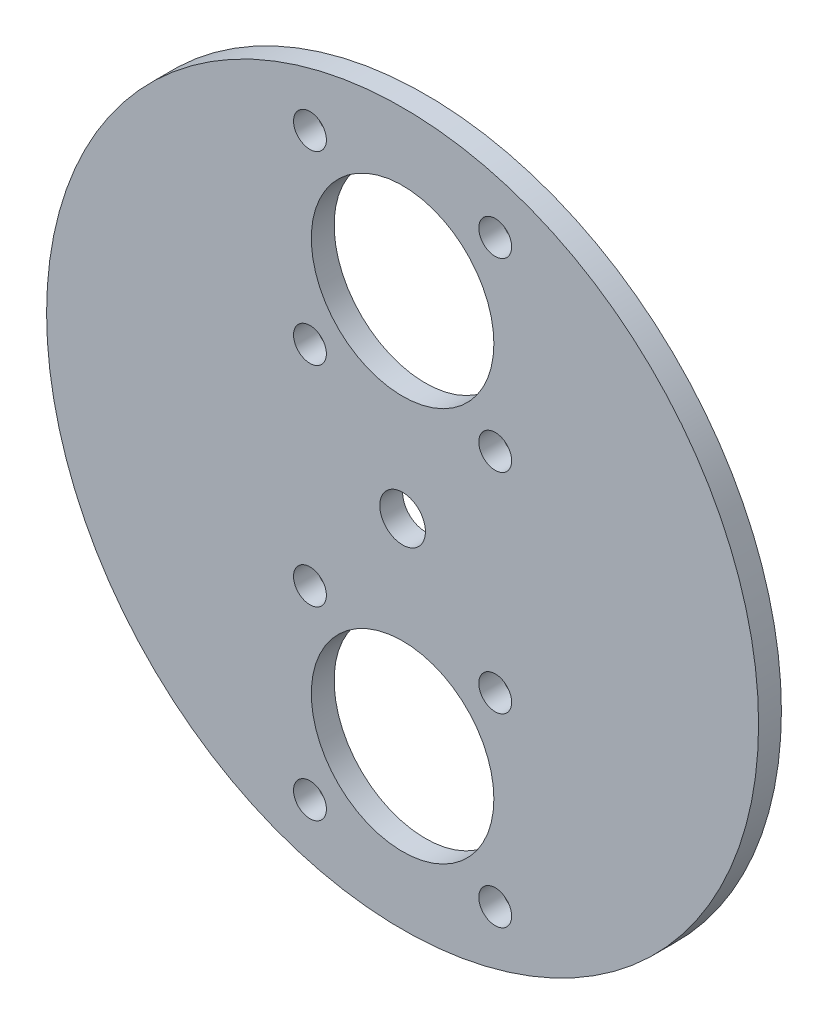
SolidWorks part; units mm, degrees
ref_plane "Front Plane" through (0, 0, 0) normal (0, 0, 1) x (1, 0, 0)
ref_plane "Top Plane" through (0, 0, 0) normal (0, 1, 0) x (1, 0, 0)
ref_plane "Right Plane" through (0, 0, 0) normal (1, 0, 0) x (0, 0, -1)
sketch "Sketch1" plane through (0, 0, 0) normal (0, 0, 1) x (1, 0, 0)
  line L0 (0, 49.53) -> (0, -49.53) construction
  circle A0 centre (0, 0) radius 49.53
  dimension "D1" = 99.06
extrude "Boss-Extrude1" add sketch "Sketch1" along normal blind 3.175 contours A0
sketch "Sketch2" plane through (0, 0, 3.175) normal (0, 0, 1) x (1, 0, 0)
  line L0 (0, 49.53) -> (0, -49.53) construction
  circle A0 centre (0, 0) radius 49.53 construction
  circle A1 centre (0, 27.432) radius 12.7
  circle A2 centre (0, -27.432) radius 12.7
  dimension "D1" = 25.4
  dimension "D2" = 25.4
  dimension "D3" = 27.432
  dimension "D4" = 27.432
extrude "Cut-Extrude1" cut sketch "Sketch2" against normal up to surface (3.175 mm away) up to face at (49.53, 0, 0)
sketch "Sketch3" plane through (0, 0, 3.175) normal (0, 0, 1) x (1, 0, 0)
  circle A0 centre (0, 0) radius 3.175
  dimension "D1" = 6.35
extrude "Cut-Extrude2" cut sketch "Sketch3" against normal up to surface (3.175 mm away) contours A0 up to face at (12.7, 27.432, 0)
sketch "Sketch5" plane through (0, 0, 0) normal (0, 0, -1) x (-1, 0, 0)
  line L0 (-12.8867, -14.5453) -> (0, -27.432) construction
  line L1 (0, 49.53) -> (0, -49.53) construction
  circle A0 centre (0, -27.432) radius 18.2245 construction
  circle A1 centre (-12.8867, -14.5453) radius 2.286
  dimension "D1" = 36.449
  dimension "D3" = 4.572
  dimension "D2" = 45
extrude "Cut-Extrude3" cut sketch "Sketch5" against normal up to surface (3.175 mm away) contours A1 up to face at (3.175, 0, 3.175)
pattern_circular "CirPattern1" count 4 over 360 about axis through (0, -27.432, 0) along (0, 0, 1) of "Cut-Extrude3"
sketch "Sketch6" plane through (0, 0, 0) normal (0, 0, -1) x (-1, 0, 0)
  line L0 (0, 27.432) -> (12.8867, 14.5453) construction
  line L1 (0, 49.53) -> (0, -49.53) construction
  circle A0 centre (0, 27.432) radius 18.2245 construction
  circle A1 centre (12.8867, 14.5453) radius 2.286
  dimension "D1" = 36.449
  dimension "D2" = 4.572
  dimension "D3" = 45
extrude "Cut-Extrude4" cut sketch "Sketch6" against normal up to surface (3.175 mm away) contours A1 up to face at (15.1727, -40.3187, 3.175)
pattern_circular "CirPattern2" count 4 over 360 about axis through (0, 27.432, 0) along (0, 0, 1) of "Cut-Extrude4"
